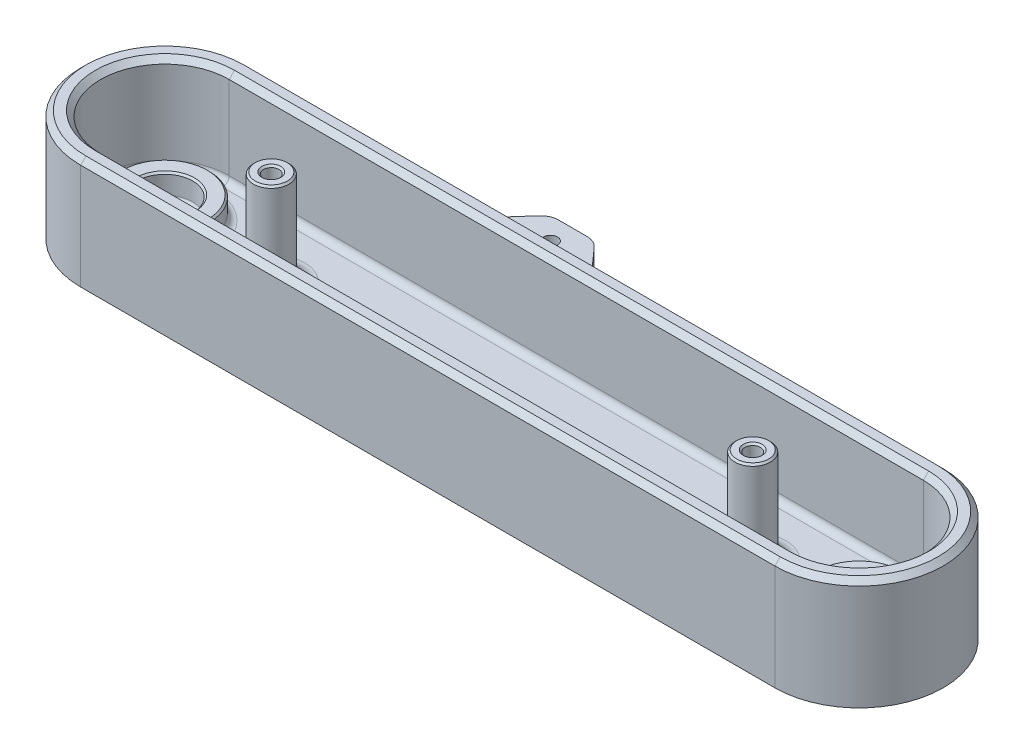
SolidWorks part; units mm, degrees
material "PLA"
ref_plane "Front Plane" through (0, 0, 0) normal (0, 0, 1) x (1, 0, 0)
ref_plane "Top Plane" through (0, 0, 0) normal (0, 1, 0) x (1, 0, 0)
ref_plane "Right Plane" through (0, 0, 0) normal (1, 0, 0) x (0, 0, -1)
sketch "Sketch1" plane through (0, 0, 0) normal (0, 1, 0) x (1, 0, 0)
  line L0 (-99.441, 0) -> (99.441, 0) construction
  line L1 (0, -55.9739) -> (0, 55.9739) construction
  line L2 (-99.441, 24.13) -> (99.441, 24.13)
  line L3 (-99.441, -24.13) -> (99.441, -24.13)
  arc A0 (-99.441, 24.13) -> (-99.441, -24.13) centre (-99.441, 0) ccw
  arc A1 (99.441, 24.13) -> (99.441, -24.13) centre (99.441, 0) cw
  point P4 (0, 0)
  point P10 (0, 0)
  dimension "D2" = 48.26
  dimension "D1" = 198.882
extrude "MainBlock" add sketch "Sketch1" along normal blind 31.75
sketch "Sketch2" plane through (0, 31.75, 0) normal (0, 1, 0) x (1, 0, 0)
  line L0 (0, 0) -> (155.7407, 0) construction
  line L1 (0, 0) -> (0, 57.4416) construction
  line L2 (-99.441, -24.13) -> (99.441, -24.13) construction
  line L3 (99.441, 24.13) -> (-99.441, 24.13) construction
  line L4 (-99.441, -24.13) -> (99.441, -24.13) construction
  line L5 (99.441, 24.13) -> (-99.441, 24.13) construction
  line L6 (-99.441, 18.415) -> (99.441, 18.415)
  line L7 (-99.441, -18.415) -> (99.441, -18.415)
  arc A0 (99.441, -24.13) -> (99.441, 24.13) centre (99.441, 0) ccw construction
  arc A1 (-99.441, 24.13) -> (-99.441, -24.13) centre (-99.441, 0) ccw construction
  arc A2 (99.441, -24.13) -> (99.441, 24.13) centre (99.441, 0) ccw construction
  arc A3 (-99.441, 24.13) -> (-99.441, -24.13) centre (-99.441, 0) ccw construction
  arc A4 (-99.441, 18.415) -> (-99.441, -18.415) centre (-99.441, 0) ccw
  arc A5 (99.441, 18.415) -> (99.441, -18.415) centre (99.441, 0) cw
  point P18 (0, 18.415)
  point P19 (0, -18.415)
  dimension "D1" = 5.715
extrude "MainPocket" cut sketch "Sketch2" against normal offset from surface (27.305 mm away) 4.445 up to face at (0, 0, 0)
sketch "Sketch3" plane through (0, 0, 0) normal (0, -1, 0) x (1, 0, 0)
  line L2 (-99.441, -24.13) -> (99.441, -24.13)
  line L3 (99.441, 24.13) -> (-99.441, 24.13)
  line L4 (-99.441, -24.13) -> (99.441, -24.13) construction
  line L5 (99.441, 24.13) -> (-99.441, 24.13) construction
  circle A0 centre (-99.441, 0) radius 4.445
  circle A1 centre (99.441, 0) radius 4.445
  arc A2 (-99.441, 24.13) -> (-99.441, -24.13) centre (-99.441, 0) ccw
  arc A3 (99.441, -24.13) -> (99.441, 24.13) centre (99.441, 0) ccw
  arc A4 (-99.441, 24.13) -> (-99.441, -24.13) centre (-99.441, 0) ccw construction
  arc A5 (99.441, -24.13) -> (99.441, 24.13) centre (99.441, 0) ccw construction
  dimension "D2" = 8.89
  dimension "D3" = 8.89
  dimension "D1" = 0
extrude "Cut-Extrude1" cut sketch "Sketch3" against normal through all
sketch "Sketch4" plane through (0, 4.445, 0) normal (0, 1, 0) x (1, 0, 0)
  line L0 (0, 0) -> (50000, 0) construction
  line L1 (0, 0) -> (0, 50000) construction
  line L2 (99.441, 18.415) -> (-99.441, 18.415)
  line L3 (-99.441, -18.415) -> (99.441, -18.415)
  line L4 (99.441, 18.415) -> (-99.441, 18.415) construction
  line L5 (-99.441, -18.415) -> (99.441, -18.415) construction
  circle A0 centre (-99.441, 0) radius 7.9566
  circle A1 centre (-99.441, 0) radius 12.7
  arc A2 (99.441, -18.415) -> (99.441, 18.415) centre (99.441, 0) ccw
  arc A3 (-99.441, 18.415) -> (-99.441, -18.415) centre (-99.441, 0) ccw
  arc A4 (99.441, -18.415) -> (99.441, 18.415) centre (99.441, 0) ccw construction
  arc A5 (-99.441, 18.415) -> (-99.441, -18.415) centre (-99.441, 0) ccw construction
  circle A6 centre (99.441, 0) radius 12.7
  circle A7 centre (99.441, 0) radius 7.9566
  dimension "D2" = 15.9131
  dimension "D3" = 25.4
  dimension "D1" = 0
extrude "Boss-Extrude1" add sketch "Sketch4" along normal blind 6.35
sketch "Sketch5" plane through (0, 0, 0) normal (0, -1, 0) x (1, 0, 0)
  line L0 (0, 0) -> (0, 50000) construction
  line L2 (-99.441, -24.13) -> (99.441, -24.13)
  line L3 (99.441, 24.13) -> (-99.441, 24.13)
  line L4 (-99.441, -24.13) -> (99.441, -24.13) construction
  line L5 (99.441, 24.13) -> (-99.441, 24.13) construction
  circle A0 centre (-99.441, 0) radius 6.35
  circle A1 centre (-99.441, 0) radius 4.445 construction
  arc A2 (-99.441, 24.13) -> (-99.441, -24.13) centre (-99.441, 0) ccw
  arc A3 (99.441, -24.13) -> (99.441, 24.13) centre (99.441, 0) ccw
  arc A4 (-99.441, 24.13) -> (-99.441, -24.13) centre (-99.441, 0) ccw construction
  arc A5 (99.441, -24.13) -> (99.441, 24.13) centre (99.441, 0) ccw construction
  circle A6 centre (-99.441, 0) radius 4.445
  circle A7 centre (99.441, 0) radius 4.445 construction
  circle A8 centre (99.441, 0) radius 6.35 construction
  dimension "D2" = 12.7
  dimension "D1" = 0
extrude "Boss-Extrude2" [suppressed] add sketch "Sketch5" along normal blind 3.81
fillet "Fillet1" [suppressed] radius 1.27
sketch "Sketch7" plane through (0, 4.445, 0) normal (0, 1, 0) x (1, 0, 0)
  line L0 (1.3556, 0) -> (50001.3556, 0) construction
  circle A0 centre (0, 0) radius 2.2225 construction
  circle A1 centre (-68.961, 0) radius 2.2225
  circle A2 centre (-99.441, 0) radius 4.445 construction
  circle A3 centre (99.441, 0) radius 4.445 construction
  circle A4 centre (99.441, 0) radius 4.445 construction
  circle A5 centre (-99.441, 0) radius 4.445 construction
  circle A6 centre (68.961, 0) radius 2.2225
  circle A7 centre (-68.961, 0) radius 5.08
  circle A8 centre (0, 0) radius 5.08 construction
  circle A9 centre (68.961, 0) radius 5.08
  dimension "D3" = 4.445
  dimension "D4" = 4.445
  dimension "D5" = 4.445
  dimension "D6" = 10.16
  dimension "D7" = 10.16
  dimension "D8" = 10.16
  dimension "D1" = 30.48
  dimension "D2" = 30.48
extrude "Boss-Extrude3" add sketch "Sketch7" along normal up to surface (27.305 mm away) up to face at (0, 31.75, 0)
fillet "Fillet2" radius 0.635 2 edges at (99.441, 4.445, 7.9566) (-99.441, 4.445, 7.9566)
fillet "Fillet3" radius 1.905 6 edges at (117.856, 4.445, 0) (0, 4.445, 18.415) (-117.856, 4.445, 0) (99.441, 4.445, -12.7) (-99.441, 4.445, 12.7) (0, 4.445, -18.415)
fillet "Fillet6" radius 4.445 2 edges at (68.961, 4.445, 5.08) (-68.961, 4.445, 5.08)
sketch "Sketch9" plane through (0, 0, 0) normal (0, -1, 0) x (1, 0, 0)
  circle A0 centre (99.441, 0) radius 4.445 construction
  circle A1 centre (99.441, 0) radius 4.445
  circle A6 centre (99.441, 0) radius 5.715
  dimension "D2" = 11.43
extrude "Bearing-Spacer" [suppressed] add sketch "Sketch9" along normal blind 8.89
fillet "Fillet7" [suppressed] radius 2.54
chamfer "Chamfer1" [suppressed] distance 0.508 angle 45
chamfer "Chamfer2" distance 0.508 angle 45 10 edges at (68.961, 31.75, 2.2225) (99.441, 4.445, 4.445) (99.441, 10.795, -12.7) (99.441, 10.795, -7.9566) (-99.441, 4.445, 4.445) (-99.441, 10.795, 12.7) (-68.961, 31.75, 5.08) (68.961, 31.75, 5.08) (-99.441, 10.795, 7.9566) (-68.961, 31.75, 2.2225)
sketch "Sketch12" plane through (0, 0, 0) normal (0, 1, 0) x (1, 0, 0)
  line L0 (-34.671, 24.13) -> (-24.511, 35.56)
  line L1 (99.441, 24.13) -> (-99.441, 24.13) construction
  line L2 (-18.161, 29.21) -> (-18.161, 24.13) construction
  line L3 (-24.511, 35.56) -> (-11.811, 35.56)
  line L4 (-34.671, 24.13) -> (-1.651, 24.13)
  line L5 (-1.651, 24.13) -> (-11.811, 35.56)
  circle A0 centre (-18.161, 29.21) radius 2.0066
  circle A1 centre (-99.441, 0) radius 4.445 construction
  point P9 (-18.161, 35.56)
  dimension "D5" = 4.0132
  dimension "D1" = 33.02
  dimension "D2" = 12.7
  dimension "D3" = 29.21
  dimension "D4" = 11.43
  dimension "D6" = 81.28
extrude "Stab_bar_Mount" add sketch "Sketch12" along normal blind 25.4
sketch "Sketch13" plane through (0, 25.4, 0) normal (0, 1, 0) x (-1, 0, 0)
  line L4 (34.671, -24.13) -> (1.651, -24.13)
  line L5 (24.511, -35.56) -> (34.671, -24.13)
  line L6 (11.811, -35.56) -> (24.511, -35.56)
  line L7 (1.651, -24.13) -> (11.811, -35.56)
  line L9 (24.511, -35.56) -> (34.671, -24.13)
  line L10 (11.811, -35.56) -> (24.511, -35.56)
  line L11 (1.651, -24.13) -> (11.811, -35.56)
  line L13 (34.671, -24.13) -> (1.651, -24.13)
  dimension "D1" = 0
chamfer "Chamfer3" distance 1.524 angle 45 8 edges at (0, 31.75, -24.13) (-123.571, 31.75, 0) (123.571, 31.75, 0) (0, 31.75, 24.13) (0, 31.75, -18.415) (-117.856, 31.75, 0) (117.856, 31.75, 0) (0, 31.75, 18.415)
chamfer "Chamfer5" [suppressed] distance 0.381 angle 45
sketch "Sketch10" plane through (0, 4.445, 0) normal (0, 1, 0) x (1, 0, 0)
  circle A0 centre (68.961, 0) radius 2.2225 construction
  circle A2 centre (-68.961, 0) radius 2.2225 construction
  circle A3 centre (68.961, 0) radius 2.2225
  circle A4 centre (0, 0) radius 2.2225 construction
  circle A5 centre (-68.961, 0) radius 2.2225
extrude "Boss-Extrude4" add sketch "Sketch10" along normal blind 16.51
sketch "Sketch11" plane through (0, 4.445, 0) normal (0, 1, 0) x (1, 0, 0)
  line L0 (-99.441, 0) -> (-9.271, 0) construction
  circle A0 centre (-9.271, 0) radius 3.175
  dimension "D1" = 6.35
  dimension "D2" = 90.17
extrude "Cut-Extrude2" cut sketch "Sketch11" against normal through all
fillet "Fillet8" radius 5.08 4 edges at (-1.651, 12.7, -24.13) (-11.811, 12.7, -35.56) (-24.511, 12.7, -35.56) (-34.671, 12.7, -24.13)
equation "\"D5@Sketch7\"=\"D3@Sketch7\""
equation "\"D4@Sketch7\"=\"D3@Sketch7\""
equation "\"D7@Sketch7\"=\"D6@Sketch7\""
equation "\"D8@Sketch7\"=\"D6@Sketch7\""
